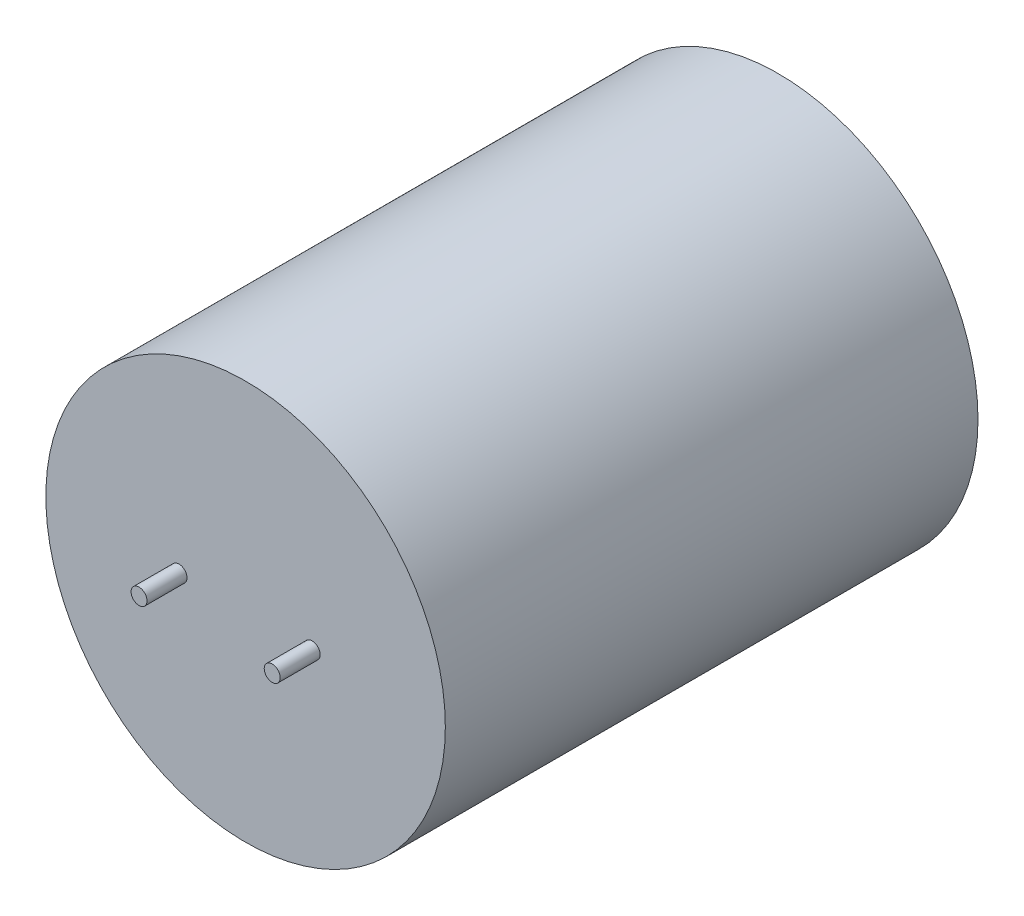
SolidWorks part; units mm, degrees
ref_plane "Спереди" through (0, 0, 0) normal (0, 0, 1) x (1, 0, 0)
ref_plane "Сверху" through (0, 0, 0) normal (0, 1, 0) x (1, 0, 0)
ref_plane "Справа" through (0, 0, 0) normal (1, 0, 0) x (0, 0, -1)
sketch "Эскиз1" plane through (0, 0, 0) normal (0, 0, 1) x (1, 0, 0)
  circle A0 centre (0, 0) radius 15
  dimension "D1" = 30
extrude "Вытянуть1" add sketch "Эскиз1" along normal blind 40
sketch "Эскиз2" plane through (0, 0, 40) normal (0, 0, 1) x (1, 0, 0)
  line L0 (0, 17.1388) -> (0, -17.9559) construction
  line L1 (-17.3108, 0) -> (19.9343, 0) construction
  circle A0 centre (-5, 0) radius 0.6
  circle A1 centre (5, 0) radius 0.6
  dimension "D1" = 1.2
  dimension "D2" = 10
extrude "Вытянуть2" add sketch "Эскиз2" along normal blind 3
